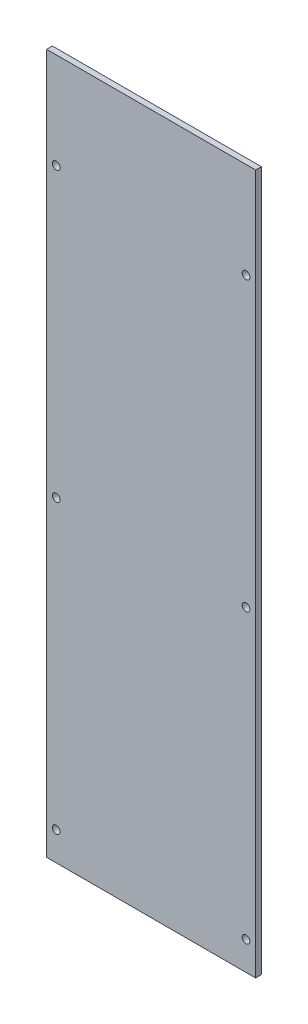
SolidWorks part; units mm, degrees
material "Acrylic (Medium-high impact)"
ref_plane "Front Plane" through (0, 0, 0) normal (0, 0, 1) x (1, 0, 0)
ref_plane "Top Plane" through (0, 0, 0) normal (0, 1, 0) x (1, 0, 0)
ref_plane "Right Plane" through (0, 0, 0) normal (1, 0, 0) x (0, 0, -1)
sketch "Sketch2" plane through (0, 0, 0) normal (0, 0, 1) x (1, 0, 0)
  line L0 (-49.5, 135) -> (-49.5, 185) construction
  line L1 (49.5, 135) -> (49.5, 185) construction
  line L2 (-54.5, 185) -> (54.5, 185)
  line L3 (0, -175) -> (0, -185) construction
  line L4 (54.5, -180) -> (-54.5, -180)
  line L5 (54.5, 185) -> (54.5, -180)
  line L6 (-54.5, 185) -> (-54.5, -180)
  circle A0 centre (-49.5, -165) radius 2
  circle A1 centre (49.5, -165) radius 2
  circle A2 centre (-49.5, -15) radius 2
  circle A3 centre (49.5, -15) radius 2
  circle A4 centre (-49.5, 135) radius 2
  circle A5 centre (49.5, 135) radius 2
  point P7 (0, 185)
  point P12 (0, -180)
  dimension "D3" = 4
  dimension "D1" = 5
  dimension "D2" = 5
  dimension "D4" = 49.5
  dimension "D5" = 135
  dimension "D6" = 185
  dimension "D7" = 15
  dimension "D8" = 165
  dimension "D9" = 180
extrude "Boss-Extrude1" add sketch "Sketch2" along normal blind 3
